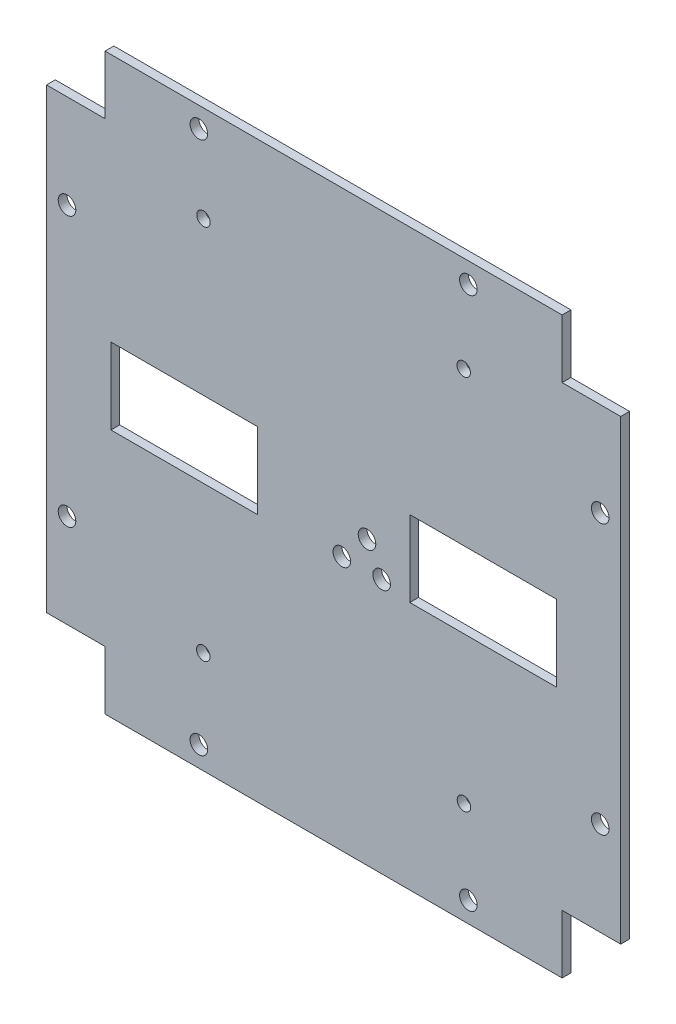
SolidWorks part; units mm, degrees
material "CFRP"
ref_plane "Front Plane" through (0, 0, 0) normal (0, 0, 1) x (1, 0, 0)
ref_plane "Top Plane" through (0, 0, 0) normal (0, 1, 0) x (1, 0, 0)
ref_plane "Right Plane" through (0, 0, 0) normal (1, 0, 0) x (0, 0, -1)
sketch "Sketch1" plane through (0, 0, 0) normal (0, 0, 1) x (1, 0, 0)
  line L1 (49, -49) -> (-49, -49)
  line L2 (49, -49) -> (49, 49)
  line L3 (49, 49) -> (-49, 49)
  line L4 (-49, -49) -> (-49, 49)
  line L5 (49, -49) -> (-49, 49) construction
  line L6 (49, 49) -> (-49, -49) construction
  point P0 (0, 0)
  dimension "D1" = 98
  dimension "D2" = 98
extrude "Boss-Extrude1" add sketch "Sketch1" along normal blind 1.5
sketch "Sketch2" plane through (0, 0, 1.5) normal (0, 0, 1) x (1, 0, 0)
  line L0 (-49, 49) -> (-49, -49) construction
  line L1 (-49, 49) -> (-39, 49)
  line L2 (-49, 49) -> (-49, 39)
  line L3 (-49, 39) -> (-39, 39)
  line L4 (-39, 49) -> (-39, 39)
  line L5 (49, 49) -> (-49, 49) construction
  line L6 (0, 0) -> (0, 56.8136) construction
  line L7 (0, 0) -> (-73.0492, 0) construction
  line L8 (39, 49) -> (39, 39)
  line L9 (49, 39) -> (39, 39)
  line L10 (49, 49) -> (49, 39)
  line L11 (49, 49) -> (39, 49)
  line L12 (49, -49) -> (39, -49)
  line L13 (49, -49) -> (49, -39)
  line L14 (49, -39) -> (39, -39)
  line L15 (39, -49) -> (39, -39)
  line L16 (-39, -49) -> (-39, -39)
  line L17 (-49, -39) -> (-39, -39)
  line L18 (-49, -49) -> (-49, -39)
  line L19 (-49, -49) -> (-39, -49)
  dimension "D1" = 10
  dimension "D2" = 10
extrude "Cut-Extrude1" cut sketch "Sketch2" against normal blind 10
hole_wizard "Ø3.0 (3) Diameter Hole1" positions "Sketch4" profile "Sketch3" hole size "Ø3.0" standard "ANSI Metric" end condition through all
sketch "Sketch4" plane through (0, 0, 0) normal (0, 0, -1) x (-1, 0, 0)
  point P0 (-23, 45.5)
  point P2 (23, 45.5)
  point P4 (45.5, 23)
  point P6 (45.5, -23)
  point P8 (23, -45.5)
  point P10 (-23, -45.5)
  point P12 (-45.5, -23)
  point P14 (-45.5, 23)
sketch "Sketch3" plane through (23, 45.5, 0) normal (1, 0, 0) x (0, 1, 0)
  line L0 (0, 0) -> (0, 1.5)
  line L1 (0, 1.5) -> (1.5, 1.5)
  line L2 (1.5, 1.5) -> (1.5, 0)
  line L5 (1.5, 0) -> (0, 0)
  line L11 (0, -6.35) -> (0, 107.95) construction
  dimension "Thru Hole Dia." = 3
  dimension "Thru Hole Depth" = 1.5
sketch "Sketch5" plane through (0, 0, 1.5) normal (0, 0, 1) x (1, 0, 0)
  line L0 (0, 0) -> (72.9008, 0) construction
  line L1 (0, 0) -> (0, 57.0834) construction
  line L11 (39, 49) -> (-39, 49) construction
  line L12 (-38, -6.5) -> (-13, -6.5)
  line L13 (-38, -6.5) -> (-38, 6.5)
  line L14 (-38, 6.5) -> (-13, 6.5)
  line L15 (-13, -6.5) -> (-13, 6.5)
  line L16 (13, -6.5) -> (13, 6.5)
  line L17 (38, 6.5) -> (13, 6.5)
  line L18 (38, -6.5) -> (38, 6.5)
  line L19 (38, -6.5) -> (13, -6.5)
  dimension "D5" = 42.5
  dimension "D6" = 55.5
  dimension "D7" = 13
  dimension "D8" = 38
extrude "Cut-Extrude2" cut sketch "Sketch5" against normal blind 10
hole_wizard "Ø2.3 (2.3) Diameter Hole1" positions "Sketch7" profile "Sketch6" hole size "Ø2.3" standard "ANSI Metric"
sketch "Sketch7" plane through (0, 0, 1.5) normal (0, 0, 1) x (1, 0, 0)
  point P0 (-22.245, -31.5907)
  point P2 (-22.2031, 32.6338)
  point P4 (22.2031, 32.6338)
  point P6 (22.245, -31.5907)
sketch "Sketch6" plane through (-22.245, -31.5907, 1.5) normal (1, 0, 0) x (0, -1, 0)
  line L0 (0, 0) -> (0, 30)
  line L1 (0, 30) -> (1.15, 30)
  line L2 (1.15, 30) -> (1.15, 0)
  line L5 (1.15, 0) -> (0, 0)
  line L10 (0, 30) -> (-1.15, 30) construction
  line L11 (0, -6.35) -> (0, 107.95) construction
  dimension "Hole Dia." = 2.3
  dimension "Hole Depth" = 30
  dimension "Drill Angle" = 180
sketch "Sketch8" plane through (0, 0, 0) normal (0, 0, -1) x (-1, 0, 0)
  circle A0 centre (-5.7, -0.8) radius 1.5
extrude "Cut-Extrude3" cut sketch "Sketch8" against normal blind 10
hole_wizard "Ø3.0 (3) Diameter Hole2" positions "Sketch10" profile "Sketch9" hole size "Ø3.0" standard "ANSI Metric"
sketch "Sketch10" plane through (0, 0, 0) normal (0, 0, -1) x (-1, 0, 0)
  point P0 (-1.4, -5.5)
  point P3 (-8.2, -5.5)
sketch "Sketch9" plane through (1.4, -5.5, 0) normal (1, 0, 0) x (0, 1, 0)
  line L0 (0, 0) -> (0, 6.5)
  line L1 (0, 6.5) -> (1.5, 6.5)
  line L2 (1.5, 6.5) -> (1.5, 0)
  line L5 (1.5, 0) -> (0, 0)
  line L10 (0, 6.5) -> (-1.5, 6.5) construction
  line L11 (0, -6.35) -> (0, 107.95) construction
  dimension "Hole Dia." = 3
  dimension "Hole Depth" = 6.5
  dimension "Drill Angle" = 180
